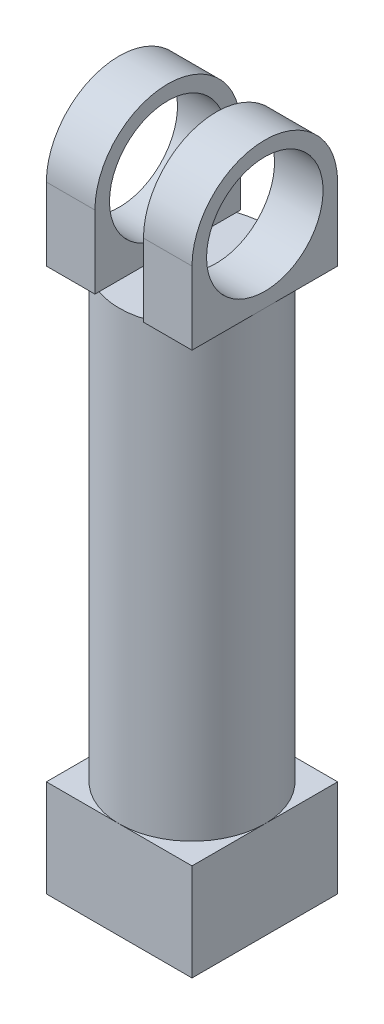
SolidWorks part; units mm, degrees
ref_plane "Front Plane" through (0, 0, 0) normal (0, 0, 1) x (1, 0, 0)
ref_plane "Top Plane" through (0, 0, 0) normal (0, 1, 0) x (1, 0, 0)
ref_plane "Right Plane" through (0, 0, 0) normal (1, 0, 0) x (0, 0, -1)
sketch "Sketch1" plane through (0, 0, 0) normal (0, 1, 0) x (1, 0, 0)
  circle A0 centre (0, 0) radius 7.5
extrude "Boss-Extrude1" add sketch "Sketch1" along normal blind 46
sketch "Sketch2" plane through (0, 0, 0) normal (0, -1, 0) x (1, 0, 0)
  line L0 (0, -7.5) -> (0, 7.5)
  line L5 (0, 7.5) -> (7.5, 7.5)
  line L6 (7.5, 7.5) -> (7.5, -7.5)
  line L7 (7.5, -7.5) -> (-7.5, -7.5)
  line L8 (-7.5, -7.5) -> (-7.5, 7.5)
  line L9 (-7.5, 7.5) -> (0, 7.5)
  circle A1 centre (0, 0) radius 7.5 construction
  circle M5 centre (0, 0) radius 7.5
extrude "Boss-Extrude2" add sketch "Sketch2" along normal blind 10 contours L0 M5 | L0 M5 | L7 L6 M5
sketch "Sketch3" plane through (-7.5, 0, 0) normal (-1, 0, 0) x (0, 0, 1)
  line L0 (0, -10) -> (0, -5)
  line L1 (-7.5, -10) -> (7.5, -10) construction
  circle A1 centre (0, -5) radius 2.5
  dimension "D1" = 5
  dimension "D2" = 5
extrude "Cut-Extrude1" cut sketch "Sketch3" against normal blind 7.5
sketch "Sketch4" plane through (0, 46, 0) normal (0, 1, 0) x (1, 0, 0)
  line L0 (0, 7.5) -> (7.5, 7.5)
  line L1 (7.5, 7.5) -> (7.5, -7.5)
  line L2 (7.5, -7.5) -> (-7.5, -7.5)
  line L3 (-7.5, -7.5) -> (-7.5, 7.5)
  line L4 (-7.5, 7.5) -> (0, 7.5)
  circle A0 centre (0, 0) radius 7.5 construction
extrude "Boss-Extrude3" add sketch "Sketch4" along normal blind 15
sketch "Sketch5" plane through (-7.5, 0, 0) normal (-1, 0, 0) x (0, 0, 1)
  line L0 (0, 61) -> (0, 53.5)
  line L1 (-7.5, 61) -> (7.5, 61) construction
  line L2 (0, 61) -> (7.5, 61)
  line L3 (7.5, 61) -> (7.5, 46)
  line L4 (7.5, 46) -> (-7.5, 46)
  line L5 (-7.5, 46) -> (-7.5, 61)
  line L6 (-7.5, 61) -> (7.5, 61)
  circle A0 centre (0, 53.5) radius 7.5
  line M6 (7.5, 61) -> (-7.5, 61)
  line M7 (-7.5, 61) -> (-7.5, 46)
  dimension "D1" = 7.5
extrude "Cut-Extrude4" cut sketch "Sketch5" against normal through all contours A0 M6 M7 | A0 L3 M6
sketch "Sketch6" plane through (-7.5, 0, 0) normal (-1, 0, 0) x (0, 0, 1)
  line L0 (0, 61) -> (0, 53.5)
  arc A0 (7.5, 53.5) -> (-7.5, 53.5) centre (0, 53.5) ccw construction
  circle A1 centre (0, 53.5) radius 6
extrude "Cut-Extrude5" cut sketch "Sketch6" against normal through all
sketch "Sketch7" plane through (-7.5, 0, 0) normal (-1, 0, 0) x (0, 0, 1)
  line L0 (-7.5, 53.5) -> (-7.5, 46)
  line L1 (-7.5, 46) -> (0, 46) construction
  line L2 (-7.5, 53.5) -> (-7.5, 46) construction
  line L3 (-7.5, 46) -> (7.5, 46)
  line L4 (7.5, 46) -> (7.5, 53.5)
  line L5 (-7.5, 53.5) -> (-7.5, 46)
  line L6 (7.5, 46) -> (7.5, 53.5)
  line L7 (7.5, 46) -> (-7.5, 46)
  circle A0 centre (0, 53.5) radius 7.5
  circle A1 centre (0, 53.5) radius 7.5
extrude "Cut-Extrude7" cut sketch "Sketch7" against normal blind 5 from offset 5 contours A0 offset against normal yes
sketch "Sketch8" plane through (-7.5, 0, 0) normal (-1, 0, 0) x (0, 0, 1)
  line L0 (-7.5, 53.5) -> (-7.5, 46)
  line L1 (-7.5, 46) -> (7.5, 46)
  line L2 (7.5, 46) -> (7.5, 53.5)
  line L3 (-7.5, 53.5) -> (-6, 53.5)
  line L4 (7.5, 53.5) -> (6, 53.5)
  circle A0 centre (0, 53.5) radius 6 construction
  circle A1 centre (0, 53.5) radius 6
  circle M1 centre (0, 53.5) radius 6
  line M2 (7.5, 46) -> (7.5, 53.5)
  line M4 (-7.5, 53.5) -> (-7.5, 46)
  line M5 (-7.5, 46) -> (0, 46)
  line M6 (0, 46) -> (7.5, 46)
extrude "Cut-Extrude8" cut sketch "Sketch8" against normal blind 5 from offset 5 contours L4 L3 M2 M1 M4 M5 M6 offset against normal yes
